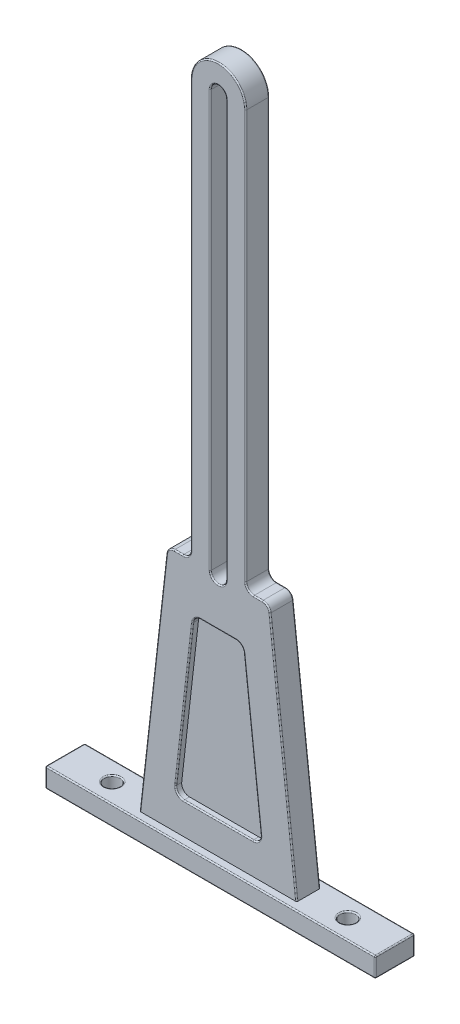
SolidWorks part; units mm, degrees
ref_plane "Front Plane" through (0, 0, 0) normal (0, 0, 1) x (1, 0, 0)
ref_plane "Top Plane" through (0, 0, 0) normal (0, 1, 0) x (1, 0, 0)
ref_plane "Right Plane" through (0, 0, 0) normal (1, 0, 0) x (0, 0, -1)
sketch "Sketch1" plane through (0, 0, 0) normal (0, 0, 1) x (1, 0, 0)
  line L0 (0, 33.5) -> (0, 86.5) construction
  line L1 (-1, 33.5) -> (-1, 86.5)
  line L2 (1, 33.5) -> (1, 86.5)
  line L3 (-3.5, 33.5) -> (-3.5, 86.5)
  line L4 (3.5, 33.5) -> (3.5, 86.5)
  arc A0 (-1, 33.5) -> (1, 33.5) centre (0, 33.5) ccw
  arc A1 (1, 86.5) -> (-1, 86.5) centre (0, 86.5) ccw
  arc A2 (3.5, 86.5) -> (-3.5, 86.5) centre (0, 86.5) ccw
  arc A3 (-3.5, 33.5) -> (3.5, 33.5) centre (0, 33.5) ccw
  point P3 (0, 60)
  point P8 (0, 0)
  point P15 (0, 0)
  point P16 (0, 87.5)
  point P17 (0, 32.5)
  dimension "D2" = 60
  dimension "D3" = 55
  dimension "D4" = 2
  dimension "D1" = 2.5
extrude "Boss-Extrude1" add sketch "Sketch1" against normal blind 3
sketch "Sketch2" plane through (0, 0, 0) normal (0, 0, 1) x (1, 0, 0)
  line L0 (-20, 0) -> (20, 0)
  line L1 (20, 0) -> (20, 2.5)
  line L2 (20, 2.5) -> (10, 2.5)
  line L3 (10, 2.5) -> (6.5, 33.5)
  line L4 (6.5, 33.5) -> (3.5, 33.5)
  line L5 (-20, 0) -> (-20, 2.5)
  line L6 (-20, 2.5) -> (-10, 2.5)
  line L7 (-10, 2.5) -> (-6.5, 33.5)
  line L8 (-6.5, 33.5) -> (-3.5, 33.5)
  arc A0 (-3.5, 33.5) -> (3.5, 33.5) centre (0, 33.5) ccw construction
  arc A2 (3.5, 33.5) -> (-3.5, 33.5) centre (0, 33.5) cw
  arc A3 (-1, 33.5) -> (1, 33.5) centre (0, 33.5) ccw construction
  point P2 (0, 0)
  dimension "D1" = 2.5
  dimension "D2" = 10
  dimension "D3" = 3
  dimension "D4" = 40
extrude "Boss-Extrude2" add sketch "Sketch2" against normal up to surface (3 mm away) up to face at (0, 60, -3)
sketch "Sketch3" plane through (0, 0, 0) normal (0, 1, 0) x (1, 0, 0)
  line L0 (20, 1.5) -> (10, 1.5) construction
  line L1 (20, 3) -> (20, 0) construction
  line L2 (10, 3) -> (10, 0) construction
  line L3 (0, 0) -> (0, -4.2545) construction
  line L4 (-20, 1.5) -> (-10, 1.5) construction
  line L5 (-20, 3) -> (-20, 0) construction
  line L6 (-10, 3) -> (-10, 0) construction
  circle A0 centre (15, 1.5) radius 1
  circle A1 centre (-15, 1.5) radius 1
  dimension "D1" = 2
extrude "Cut-Extrude1" cut sketch "Sketch3" along normal up to surface (2.5 mm away) up to face at (15, 2.5, -1.5)
sketch "Sketch4" plane through (0, 0, 0) normal (0, 1, 0) x (1, 0, 0)
  line L21 (3.5, 3) -> (-3.5, 3) construction
  line L23 (-21, 4) -> (21, 4)
  line L24 (-21, 4) -> (-21, -1)
  line L25 (-21, -1) -> (21, -1)
  line L26 (21, 4) -> (21, -1)
  line L27 (-20, 3) -> (-20, 0) construction
  line L28 (6.5, 0) -> (3.5, 0) construction
  line L29 (20, 3) -> (20, 0) construction
  circle A0 centre (15, 1.5) radius 1 construction
  circle A1 centre (-15, 1.5) radius 1 construction
  circle A2 centre (15, 1.5) radius 1
  circle A3 centre (-15, 1.5) radius 1
  dimension "D1" = 1
  dimension "D2" = 1
  dimension "D3" = 1
  dimension "D4" = 1
extrude "Boss-Extrude3" add sketch "Sketch4" along normal up to surface (2.5 mm away) up to face at (-16, 2.5, -1.5)
fillet "Fillet1" radius 1 4 edges at (3.5, 33.5, -1.5) (6.5, 33.5, -1.5) (-6.5, 33.5, -1.5) (-3.5, 33.5, -1.5)
sketch "Sketch5" plane through (0, 0, 0) normal (0, 0, 1) x (1, 0, 0)
  line L0 (-5.523, 6.5) -> (5.523, 6.5)
  line L1 (5.523, 6.5) -> (3.152, 27.5)
  line L2 (3.152, 27.5) -> (-3.152, 27.5)
  line L3 (-3.152, 27.5) -> (-5.523, 6.5)
  line L4 (10, 2.5) -> (6.6002, 32.6122) construction
  line L5 (10, 2.5) -> (-10, 2.5) construction
  line L6 (-6.6002, 32.6122) -> (-10, 2.5) construction
  dimension "D1" = 4
  dimension "D2" = 27.5
  dimension "D3" = 4
  dimension "D4" = 4
  dimension "D5" = 4
  dimension "D6" = 4
extrude "Cut-Extrude2" cut sketch "Sketch5" against normal blind 0.75
sketch "Sketch6" plane through (0, 0, -3) normal (0, 0, -1) x (-1, 0, 0)
  line L0 (-5.523, 6.5) -> (5.523, 6.5)
  line L1 (5.523, 6.5) -> (3.152, 27.5)
  line L2 (3.152, 27.5) -> (-3.152, 27.5)
  line L3 (-3.152, 27.5) -> (-5.523, 6.5)
  line L4 (-21, 2.5) -> (21, 2.5) construction
  line L5 (10, 2.5) -> (6.6002, 32.6122) construction
  line L6 (-6.6002, 32.6122) -> (-10, 2.5) construction
  dimension "D1" = 27.5
  dimension "D2" = 4
  dimension "D3" = 4
  dimension "D4" = 4
  dimension "D5" = 4
  dimension "D6" = 4
extrude "Cut-Extrude3" cut sketch "Sketch6" against normal blind 0.75
fillet "Fillet2" radius 1 8 edges at (3.152, 27.5, -2.625) (-3.152, 27.5, -2.625) (5.523, 6.5, -2.625) (-5.523, 6.5, -2.625) (-3.152, 27.5, -0.375) (3.152, 27.5, -0.375) (5.523, 6.5, -0.375) (-5.523, 6.5, -0.375)
fillet "Fillet3" radius 0.15 62 edges at (4.3248, 17.1122, -3) (0, 6.5, -3) (-4.3248, 17.1122, -3) (0, 27.5, -3) (-4.3248, 17.1122, 0) (0, 6.5, 0) (4.3248, 17.1122, 0) (0, 27.5, 0) (0, 2.5, -4) (21, 2.5, -1.5) (0, 2.5, 1) (-21, 2.5, -1.5) (-21, 0, -1.5) (21, 0, -1.5) (0, 0, -4) (-21, 1.25, -4) (21, 1.25, -4) (21, 1.25, 1) (-21, 1.25, 1) (-15, 0, -2.5) (-16, 2.5, -1.5) (15, 0, -0.5) (14, 2.5, -1.5) (8.3001, 17.5561, -3) (8.3001, 17.5561, 0) (5.0533, 33.5, -3) (5.0533, 33.5, 0) (-5.0533, 33.5, -3) (-5.0533, 33.5, 0) (-8.3001, 17.5561, 0) (-8.3001, 17.5561, -3) (0, 32.5, 0) (1, 60, 0) (0, 87.5, 0) (-1, 60, 0) (0, 32.5, -3) (1, 60, -3) (0, 87.5, -3) (-1, 60, -3) (3.5, 60.5, 0) (0, 90, 0) (-3.5, 60.5, 0) (3.5, 60.5, -3) (0, 90, -3) (-3.5, 60.5, -3) (-6.2728, 33.2457, 0) (6.2728, 33.2457, 0) (-6.2728, 33.2457, -3) (6.2728, 33.2457, -3) (3.7929, 33.7929, 0) (3.7929, 33.7929, -3) (-3.7929, 33.7929, 0) (-3.7929, 33.7929, -3) (2.9248, 27.2457, -3) (-2.9248, 27.2457, -3) (5.1494, 6.8337, -3) (-5.1494, 6.8337, -3) (-2.9248, 27.2457, 0) (2.9248, 27.2457, 0) (5.1494, 6.8337, 0) (-5.1494, 6.8337, 0) (0, 0, 1)
